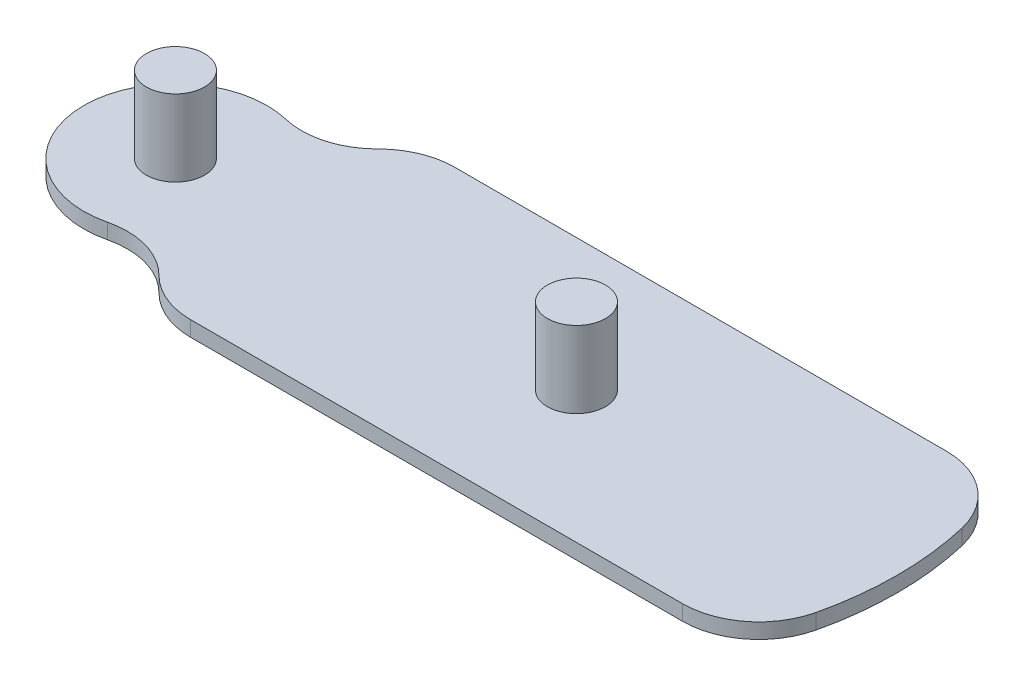
SolidWorks part; units mm, degrees
ref_plane "Front Plane" through (0, 0, 0) normal (0, 0, 1) x (1, 0, 0)
ref_plane "Top Plane" through (0, 0, 0) normal (0, 1, 0) x (1, 0, 0)
ref_plane "Right Plane" through (0, 0, 0) normal (1, 0, 0) x (0, 0, -1)
sketch "Sketch1" plane through (0, 0, 0) normal (0, 1, 0) x (1, 0, 0)
  line L0 (0, 0) -> (52.5, 0)
  circle A0 centre (0, 0) radius 9.25
  circle A1 centre (0, 0) radius 12
  circle A2 centre (52.5, 0) radius 42
  circle A3 centre (52.5, 0) radius 39.25
  dimension "D1" = 18.5
  dimension "D3" = 24
  dimension "D4" = 78.5
  dimension "D5" = 84
  dimension "D2" = 52.5
extrude "Boss-Extrude1" add sketch "Sketch1" along normal blind 2
sketch "Sketch2" plane through (0, 2, 0) normal (0, 1, 0) x (1, 0, 0)
  circle A0 centre (0, 0) radius 3.8
  circle A1 centre (52.5, 0) radius 3.8
  dimension "D1" = 7.6
  dimension "D2" = 7.6
extrude "Boss-Extrude2" add sketch "Sketch2" along normal blind 10
fillet "Fillet1" radius 10 2 edges at (10.8214, 1, 5.1862) (10.8214, 1, -5.1862)
sketch "Sketch3" plane through (0, 2, 0) normal (0, 1, 0) x (1, 0, 0)
  line L0 (14.2212, -17.2838) -> (90.7788, -17.2838)
  line L1 (14.2212, 17.2838) -> (90.7788, 17.2838)
  arc A0 (14.2212, -17.2838) -> (90.7788, -17.2838) centre (52.5, 0) ccw
  arc A1 (90.7788, 17.2838) -> (14.2212, 17.2838) centre (52.5, 0) ccw
extrude "Cut-Extrude1" cut sketch "Sketch3" against normal blind 10
fillet "Fillet2" radius 10 4 edges at (14.2212, 1, -17.2838) (90.7788, 1, -17.2838) (90.7788, 1, 17.2838) (14.2212, 1, 17.2838)
